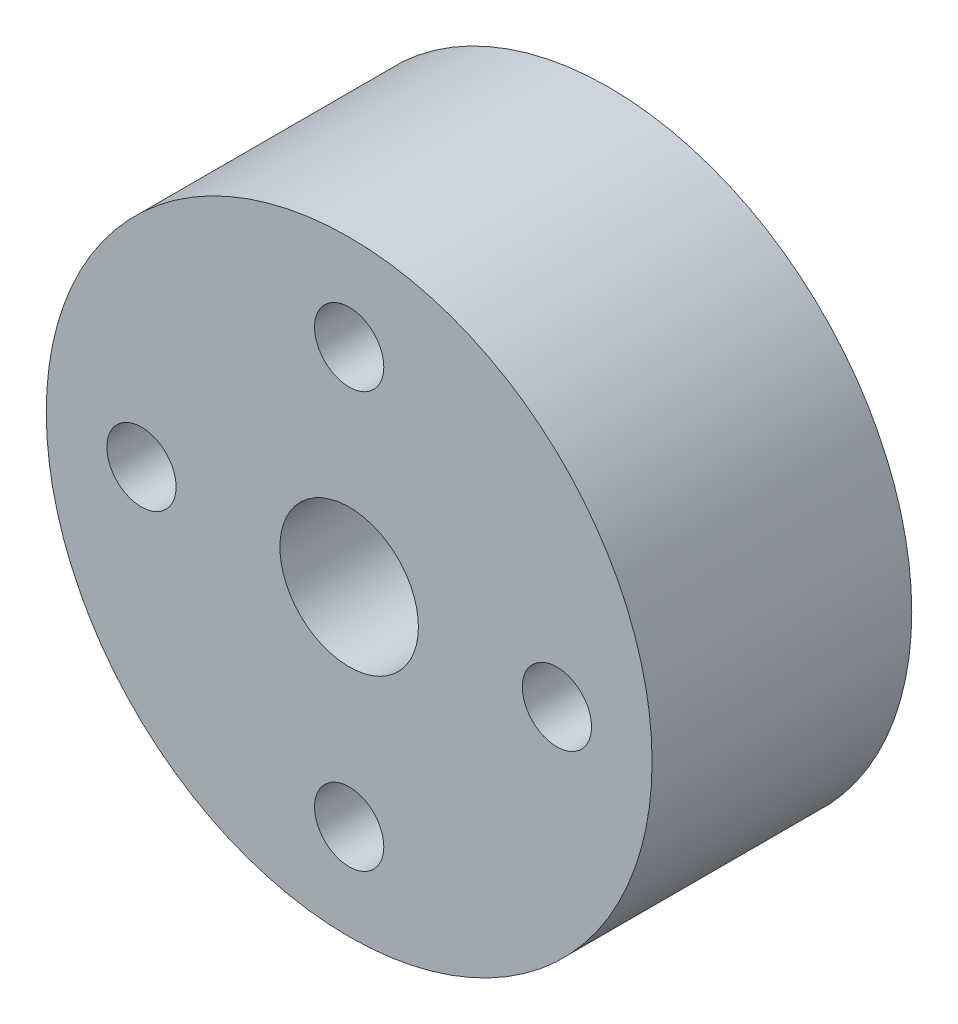
SolidWorks part; units mm, degrees
ref_plane "Front Plane" through (0, 0, 0) normal (0, 0, 1) x (1, 0, 0)
ref_plane "Top Plane" through (0, 0, 0) normal (0, 1, 0) x (1, 0, 0)
ref_plane "Right Plane" through (0, 0, 0) normal (1, 0, 0) x (0, 0, -1)
sketch "Sketch1" plane through (0, 0, 0) normal (0, 0, 1) x (1, 0, 0)
  circle A0 centre (0, 0) radius 17.5
  circle A1 centre (0, 0) radius 4
  circle A2 centre (12, 0) radius 2
  circle A3 centre (0, -12) radius 2
  circle A4 centre (-12, 0) radius 2
  circle A5 centre (0, 12) radius 2
  point P15 (0, 0)
  dimension "D1" = 8
  dimension "D2" = 4
  dimension "D4" = 35
  dimension "D3" = 12
  dimension "D5" = 4
extrude "Boss-Extrude1" add sketch "Sketch1" along normal blind 15
sketch "Sketch2" plane through (0, 0, 15) normal (0, 0, 1) x (1, 0, 0)
  line L0 (-12, 0) -> (12, 0)
